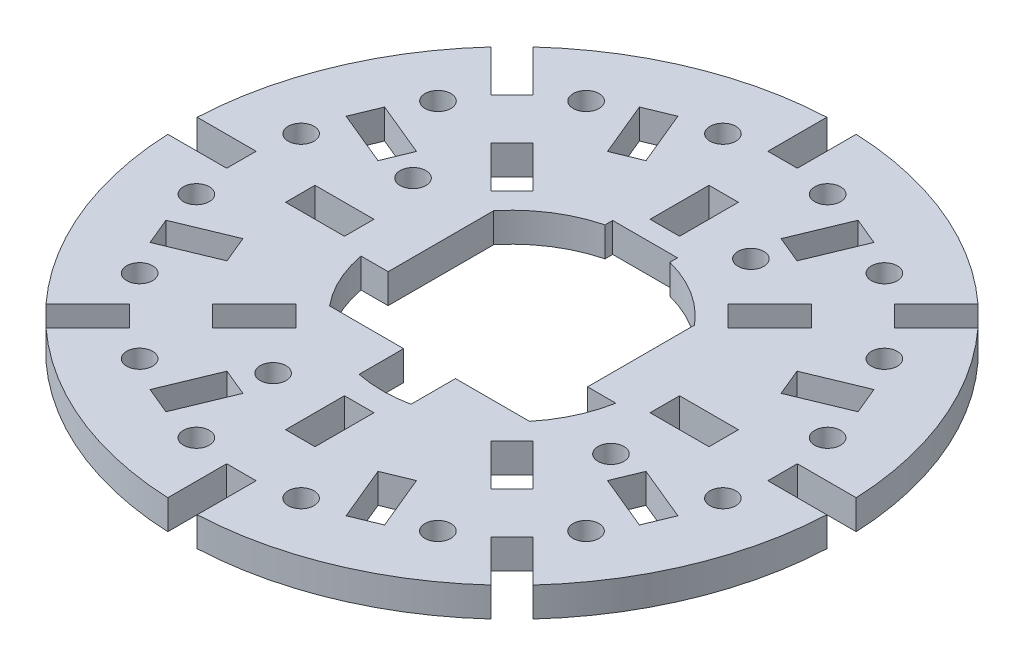
SolidWorks part; units mm, degrees
ref_plane "Front" through (0, 0, 0) normal (0, 0, 1) x (1, 0, 0)
ref_plane "Top" through (0, 0, 0) normal (0, 1, 0) x (1, 0, 0)
ref_plane "Right" through (0, 0, 0) normal (1, 0, 0) x (0, 0, -1)
sketch "Sketch1" plane through (0, 0, 0) normal (0, 1, 0) x (1, 0, 0)
  line L0 (-3.4925, 13.5264) -> (-3.4925, 14.351)
  line L1 (-3.4925, 14.351) -> (3.4925, 14.351)
  line L2 (3.4925, 14.351) -> (3.4925, 13.5264)
  line L3 (0, 14.351) -> (0, -13.97) construction
  circle A0 centre (0, 0) radius 13.97
  circle A1 centre (0, 0) radius 35.56
  circle A2 centre (-13.97, 0) radius 0.127
  dimension "D1" = 27.94
  dimension "D2" = 71.12
  dimension "D5" = 28.067
  dimension "D3" = 28.321
  dimension "D4" = 6.985
extrude "Boss-Extrude1" add sketch "Sketch1" along normal mid plane 3.175 contours A1 A2 A0 L0 L1 L2
sketch "Sketch2" plane through (0, 1.5875, 0) normal (0, 1, 0) x (1, 0, 0)
  line L0 (0, 35.56) -> (0, 16.4745) construction
  line L1 (-1.5875, 16.4745) -> (1.5875, 16.4745)
  line L2 (1.5875, 16.4745) -> (1.5875, 35.5245)
  line L3 (-1.5875, 16.4745) -> (-1.5875, 35.5245)
  line L4 (-1.5875, 22.8245) -> (1.5875, 22.8245)
  line L5 (-1.5875, 29.1745) -> (1.5875, 29.1745)
  circle A0 centre (0, 0) radius 35.56 construction
  arc A1 (-1.5875, 35.5245) -> (1.5875, 35.5245) centre (0, 0) cw
  circle M7 centre (0, 0) radius 35.56
  dimension "D1" = 3.175
  dimension "D2" = 19.05
  dimension "D3" = 6.35
  dimension "D4" = 6.35
extrude "Cut-Extrude1" cut sketch "Sketch2" against normal through all contours L0 L5 L2 M7 | L0 A1 L3 L5 | L0 L4 L3 L1 | L4 L0 L1 L2
pattern_circular "CirPattern1" count 8 over 360 about axis through (0, 0, 0) along (0, 1, 0) of "Cut-Extrude1"
sketch "Sketch3" plane through (0, 1.5875, 0) normal (0, 1, 0) x (1, 0, 0)
  line L0 (-13.7372, -2.54) -> (-10.8162, -2.54)
  line L1 (-10.8162, -2.54) -> (-10.8162, 8.8415)
  line L2 (13.7372, -2.54) -> (10.6892, -2.54)
  line L3 (10.6892, -2.54) -> (10.6892, 8.9946)
  line L4 (-10.7763, -8.89) -> (-2.794, -8.89)
  line L5 (-2.794, -8.89) -> (-2.794, -13.6877)
  line L6 (2.794, -13.6877) -> (2.794, -8.89)
  line L7 (2.794, -8.89) -> (10.7763, -8.89)
  arc A0 (-13.9694, -0.127) -> (3.4925, 13.5264) centre (0, 0) ccw construction
  arc A1 (-3.4925, 13.5264) -> (-13.9694, 0.127) centre (0, 0) ccw construction
  arc A2 (-13.9694, 0.127) -> (-13.9694, -0.127) centre (-13.97, 0) ccw construction
  arc A3 (-13.9694, 0.127) -> (-13.9694, -0.127) centre (-13.97, 0) ccw
  arc A4 (-13.9694, -0.127) -> (3.4925, 13.5264) centre (0, 0) ccw
  arc A5 (-3.4925, 13.5264) -> (-13.9694, 0.127) centre (0, 0) ccw
  dimension "D1" = 2.921
  dimension "D2" = 3.048
  dimension "D3" = 11.43
  dimension "D4" = 5.08
  dimension "D5" = 5.588
extrude "Boss-Extrude2" add sketch "Sketch3" against normal up to vertex (3.175 mm away) up to point (-3.4925, -1.5875, -13.5264)
sketch "Sketch4" plane through (0, 1.5875, 0) normal (0, 1, 0) x (1, 0, 0)
  line L0 (16.4745, 1.5875) -> (22.8245, 1.5875) construction
  line L1 (1.5875, 19.6495) -> (12.7718, 15.0169) construction
  line L2 (1.5875, 16.4745) -> (1.5875, 22.8245) construction
  line L3 (10.5267, 12.7718) -> (15.0169, 17.2619) construction
  line L4 (7.1796, 17.3332) -> (7.5441, 18.213) construction
  circle A0 centre (0, 0) radius 19.7136 construction
  circle A1 centre (7.5441, 18.213) radius 1.397
  point P3 (19.6495, 1.5875)
  dimension "D1" = 2.794
extrude "Cut-Extrude2" cut sketch "Sketch4" against normal blind 3.175
pattern_circular "CirPattern2" count 4 over 360 about axis through (0, 0, 0) along (0, 1, 0) of "Cut-Extrude2"
sketch "Sketch5" plane through (0, 1.5875, 0) normal (0, 1, 0) x (1, 0, 0)
  line L0 (0, 0) -> (-32.8532, 13.6082) construction
  line L1 (-26.379, 12.6448) -> (-27.594, 9.7115)
  line L2 (-27.594, 9.7115) -> (-21.7274, 7.2815)
  line L3 (-21.7274, 7.2815) -> (-20.5124, 10.2148)
  line L4 (-20.5124, 10.2148) -> (-26.379, 12.6448)
  arc A0 (-26.2422, 23.9971) -> (-35.5245, 1.5875) centre (0, 0) ccw construction
  point P8 (-26.9865, 11.1782)
  dimension "D1" = 6.35
  dimension "D2" = 6.35
  dimension "D3" = 3.175
extrude "Cut-Extrude3" cut sketch "Sketch5" against normal through all
pattern_circular "CirPattern3" count 8 over 360 about axis through (0, 0, 0) along (0, 1, 0) of "Cut-Extrude3"
sketch "Sketch6" plane through (0, 1.5875, 0) normal (0, 1, 0) x (1, 0, 0)
  line L2 (-19.507, 21.7521) -> (-12.6448, 26.379) construction
  circle A0 centre (-16.0759, 24.0655) radius 1.397
  dimension "D1" = 2.794
extrude "Cut-Extrude4" cut sketch "Sketch6" against normal through all
pattern_circular "CirPattern4" count 16 over 360 about axis through (0, 0, 0) along (0, 1, 0) of "Cut-Extrude4"
